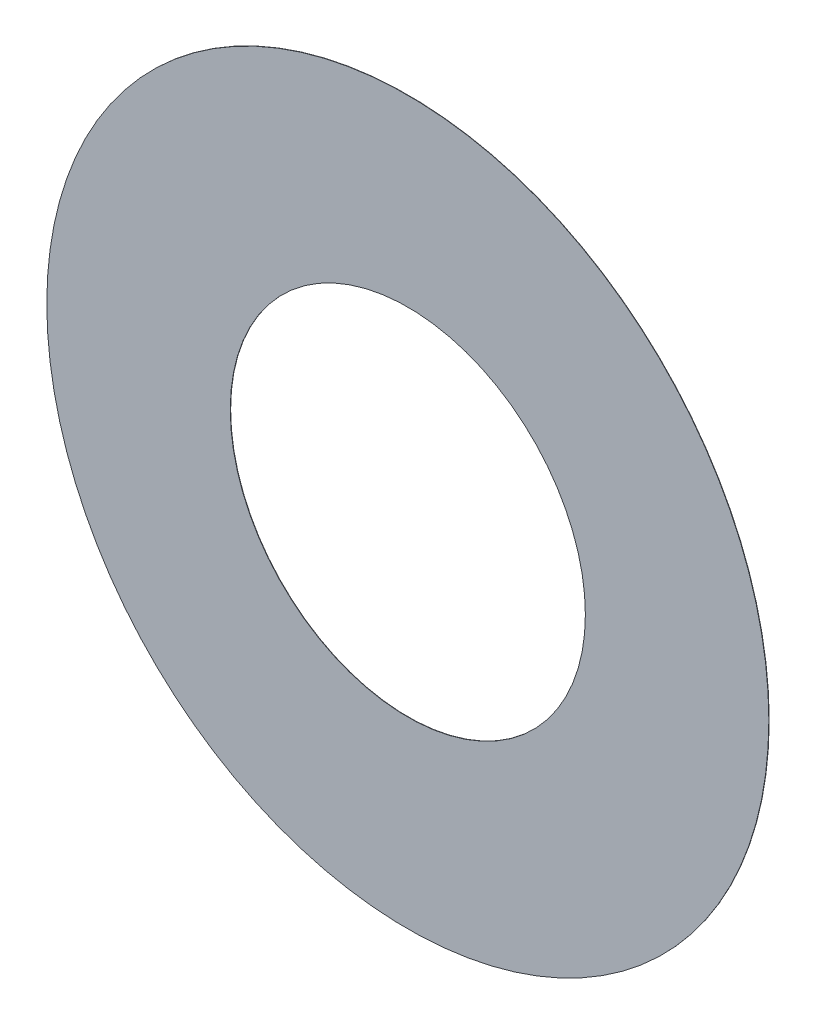
SolidWorks part; units mm, degrees
ref_plane "Front Plane" through (0, 0, 0) normal (0, 0, 1) x (1, 0, 0)
ref_plane "Top Plane" through (0, 0, 0) normal (0, 1, 0) x (1, 0, 0)
ref_plane "Right Plane" through (0, 0, 0) normal (1, 0, 0) x (0, 0, -1)
sketch "Sketch1" plane through (0, 0, 0) normal (0, 0, 1) x (1, 0, 0)
  circle A0 centre (0, 0) radius 77.47
  circle A2 centre (0, 0) radius 38.1
  dimension "D1" = 154.94
  dimension "D2" = 76.2
extrude "Boss-Extrude1" add sketch "Sketch1" along normal blind 0.0762
